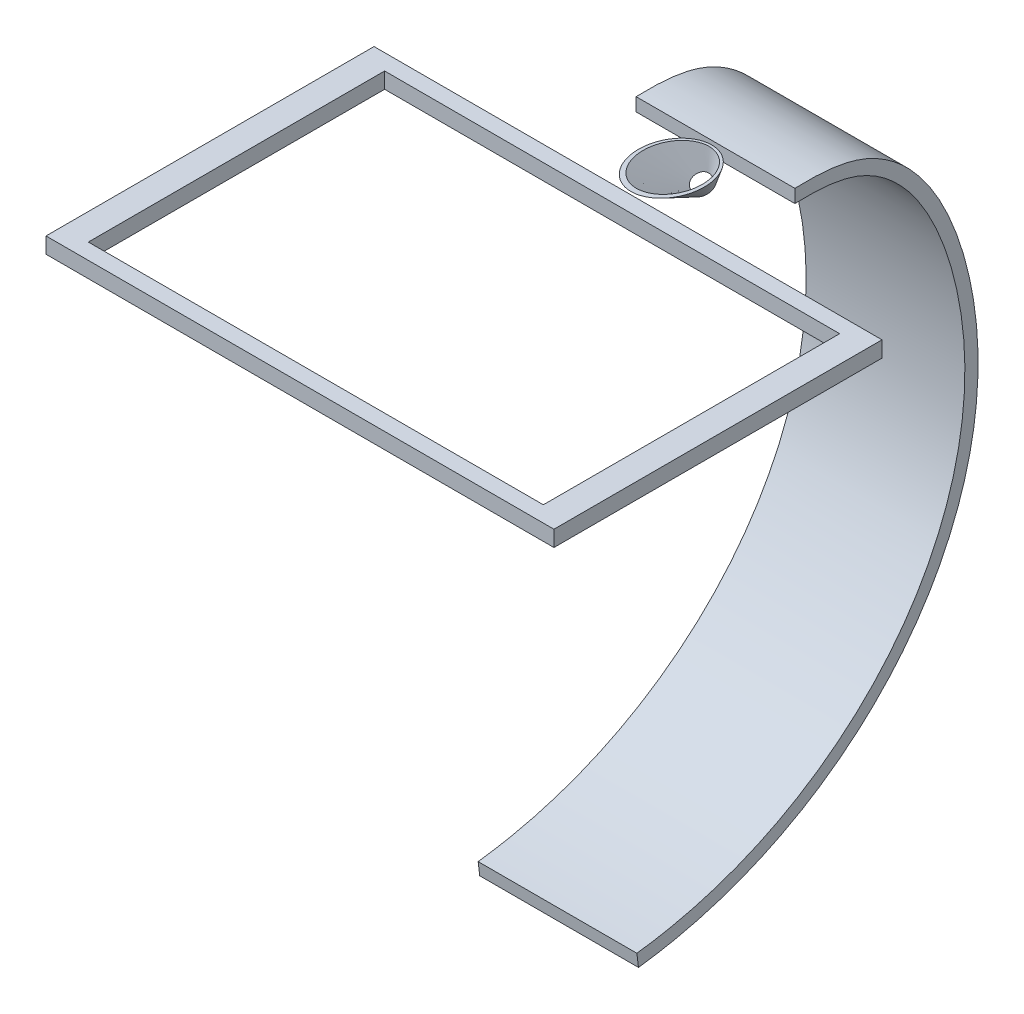
SolidWorks part; units mm, degrees
ref_plane "Front" through (0, 0, 0) normal (0, 0, 1) x (1, 0, 0)
ref_plane "Top" through (0, 0, 0) normal (0, 1, 0) x (1, 0, 0)
ref_plane "Right" through (0, 0, 0) normal (1, 0, 0) x (0, 0, -1)
sketch "Sketch1" plane through (0, 0, 0) normal (0, 1, 0) x (1, 0, 0)
  line L1 (-43, -28) -> (43, -28)
  line L2 (-43, -28) -> (-43, 28)
  line L3 (-43, 28) -> (43, 28)
  line L4 (43, -28) -> (43, 28)
  line L5 (-43, -28) -> (43, 28) construction
  line L6 (-43, 28) -> (43, -28) construction
  line L7 (-48, -31) -> (48, -31)
  line L8 (-48, -31) -> (-48, 31)
  line L9 (-48, 31) -> (48, 31)
  line L10 (48, -31) -> (48, 31)
  line L11 (-48, -31) -> (48, 31) construction
  line L12 (-48, 31) -> (48, -31) construction
  point P0 (0, 0)
  point P6 (0, 0)
  dimension "D1" = 86
  dimension "D2" = 56
  dimension "D3" = 3
  dimension "D4" = 5
extrude "Boss-Extrude1" add sketch "Sketch1" along normal blind 3
sketch "Sketch4" plane through (0, 0, 0) normal (1, 0, 0) x (0, 0, -1)
  line L0 (45.6947, -3.6988) -> (-61.4431, 55.6887) construction
  line L1 (45.6947, -3.6988) -> (-61.4431, 55.6887) construction
  line L2 (32.8171, -9.0552) -> (52.2183, 2.1461) construction
  line L3 (32.8171, -9.0552) -> (52.2183, 2.1461) construction
  line L4 (45.6947, -3.6988) -> (47.8326, 118.7791) construction
  line L5 (45.6947, -3.6988) -> (47.8326, 118.7791) construction
sketch "Sketch5" plane through (0, 0, 0) normal (1, 0, 0) x (0, 0, -1)
  line L0 (45.6947, -3.6988) -> (38.2413, 9.211) construction
  line L1 (32.8171, -9.0552) -> (52.2183, 2.1461) construction
  line L2 (45.6947, -3.6988) -> (-61.4431, 55.6887) construction
  line L3 (43.8581, -2.6807) -> (35.4738, 1.9668)
  line L4 (43.8581, -2.6807) -> (35.4738, 1.9668)
  line L7 (42.8478, -3.264) -> (29.3973, 4.1917)
  line L8 (29.3973, 4.1917) -> (35.4738, 1.9668)
  line L9 (42.8478, -3.264) -> (43.8581, -2.6807)
  line L10 (43.6157, -3.118) -> (32.4355, 3.0793)
  line L11 (43.6157, -3.118) -> (35.2314, 1.5295) construction
  dimension "D1" = 0.5
  dimension "D2" = 0.5
revolve "Revolve4" add sketch "Sketch5" angle 360 about L0
sketch "Sketch6" plane through (0, 0, -31) normal (0, 0, -1) x (-1, 0, 0)
  line L1 (48, 3) -> (-48, 3)
  line L2 (48, 3) -> (48, 16.2937)
  line L3 (48, 16.2937) -> (-48, 16.2937)
  line L4 (-48, 0) -> (48, 0)
  line L5 (48, 0) -> (48, 3)
  line L6 (48, 3) -> (-48, 3)
  line L7 (-48, 3) -> (-48, 0)
  line L8 (-48, 0) -> (48, 0)
  line L9 (48, 0) -> (48, 3)
  line L10 (48, 3) -> (-48, 3)
  line L11 (-48, 3) -> (-48, 0)
  line L12 (-48, 3) -> (-48, 16.2937)
  line M7 (48, 3) -> (-48, 3)
  dimension "D1" = 0
extrude "Cut-Extrude1" cut sketch "Sketch6" along normal through all and the other way through all contours L12 L2 L3 M7
sketch "Sketch7" plane through (0, 0, 0) normal (1, 0, 0) x (0, 0, -1)
  line L13 (32.8171, -19.124) -> (32.8171, -24.1806)
  line L14 (32.8171, -24.1806) -> (37.3171, -21.5825)
  line L15 (37.3171, -21.5825) -> (37.3171, -14.2513)
  line L16 (37.3171, -14.2513) -> (39.4389, -13.0263)
  line L17 (39.4389, -13.0263) -> (38.4389, -11.2943)
  line L18 (38.4389, -11.2943) -> (55.846, -1.2443)
  line L19 (55.846, -1.2443) -> (56.846, -2.9763)
  line L20 (56.846, -2.9763) -> (58.9678, -1.7513)
  line L21 (58.9678, -1.7513) -> (58.5928, -1.1018)
  line L22 (52.2183, 2.1461) -> (32.8171, -9.0552)
  line L23 (32.8171, -9.0552) -> (32.8171, -16.2372)
  line L24 (32.8171, -16.2372) -> (27.8171, -19.124)
  line L25 (27.8171, -19.124) -> (32.8171, -19.124)
  line L26 (32.8171, -19.124) -> (32.8171, -24.1806)
  line L27 (32.8171, -24.1806) -> (37.3171, -21.5825)
  line L28 (37.3171, -21.5825) -> (37.3171, -14.2513)
  line L29 (37.3171, -14.2513) -> (39.4389, -13.0263)
  line L30 (39.4389, -13.0263) -> (38.4389, -11.2943)
  line L31 (38.4389, -11.2943) -> (55.846, -1.2443)
  line L32 (55.846, -1.2443) -> (56.846, -2.9763)
  line L33 (56.846, -2.9763) -> (58.9678, -1.7513)
  line L34 (58.9678, -1.7513) -> (58.5928, -1.1018)
  line L35 (52.2183, 2.1461) -> (32.8171, -9.0552)
  line L36 (32.8171, -9.0552) -> (32.8171, -16.2372)
  line L37 (32.8171, -16.2372) -> (27.8171, -19.124)
  line L38 (27.8171, -19.124) -> (32.8171, -19.124)
  line L53 (58.5928, -1.1018) -> (52.2183, 2.1461)
  line L54 (58.5928, -1.1018) -> (52.2183, 2.1461)
  dimension "D1" = 0
sketch "Sketch8" plane through (0, 0, 0) normal (1, 0, 0) x (0, 0, -1)
  line L2 (46.7417, -1.0158) -> (46.8118, 3) construction
  line L4 (-31, 0) -> (31, 0)
  line L5 (31, 0) -> (31, 3)
  line L6 (31, 3) -> (-31, 3)
  line L7 (-31, 3) -> (-31, 0)
  line L8 (-31, 0) -> (31, 0)
  line L11 (-31, 3) -> (-31, 0)
  line L12 (-35, 7.198) -> (-35, -4)
  line L15 (-31, 2.5) -> (31, 2.5)
  line L16 (47.5312, 3.031) -> (47.5312, 0.5296)
  line L18 (17.6704, -107.2402) -> (17.9773, -109.7213)
  line L25 (-35, -4) -> (31, -4) construction
  line L26 (31, -4) -> (196.6797, -4) construction
  line L29 (31, 0) -> (31.0681, 0) construction
  line L30 (31.0681, 0) -> (-31, 3) construction
  line L31 (196.6797, -4) -> (-35, 7.198) construction
  spline S0 degree 3 poles (31.0681, 0) (39.2616, -0.8727) (64.8569, 6.1362) (83.7032, -33.9651) (74.4322, -82.4857) (41.8152, -104.2537) (17.6704, -107.2402) knots 0 0 0 0 0.161872 0.37793 0.6219 1 1 1 1
  spline S1 degree 1 poles (31.3329, 2.4859) (17.9773, -109.7213) knots 0 0 1 1 construction
  spline S2 degree 3 poles (31.3329, 2.4859) (31.6969, 2.4472) (32.4142, 2.3882) (33.9523, 2.3236) (35.9853, 2.3391) (38.5828, 2.4677) (41.9317, 2.704) (45.4199, 2.961) (49.2514, 3.0962) (53.3847, 3.0159) (57.4792, 2.4307) (61.1315, 1.1545) (64.5235, -0.5792) (68.3029, -3.4951) (73.3809, -9.3848) (78.0753, -18.4595) (81.3839, -30.5483) (82.5085, -42.3505) (81.5804, -53.6922) (78.7417, -64.418) (74.1424, -74.3727) (67.936, -83.4098) (60.2758, -91.3886) (51.3132, -98.1728) (42.8825, -102.7184) (35.6366, -105.6227) (29.9653, -107.4186) (24.0946, -108.8129) (20.0129, -109.4695) (17.9773, -109.7213) knots 0 0 0 0 0.007812 0.015625 0.03125 0.046875 0.0625 0.089111 0.104736 0.125 0.15625 0.171875 0.1875 0.21875 0.25 0.3125 0.375 0.4375 0.5 0.5625 0.625 0.6875 0.75 0.8125 0.875 0.90625 0.9375 0.96875 1 1 1 1
  dimension "D4" = 2.5
  dimension "D1" = 0
  dimension "D2" = 4
  dimension "D3" = 2.5
extrude "Boss-Extrude4" add sketch "Sketch8" along normal blind 15 and the other way blind 15 separate body
sketch "Sketch10" plane through (0, 3, 0) normal (0, 1, 0) x (1, 0, 0)
  line L4 (48, -31) -> (48, 31)
  line L5 (48, 31) -> (-48, 31)
  line L6 (-48, 31) -> (-48, -31)
  line L7 (-48, -31) -> (48, -31)
  line L8 (48, -31) -> (48, 31)
  line L9 (48, 31) -> (-48, 31)
  line L10 (-48, 31) -> (-48, -31)
  line L11 (-48, -31) -> (48, -31)
  dimension "D1" = 0
